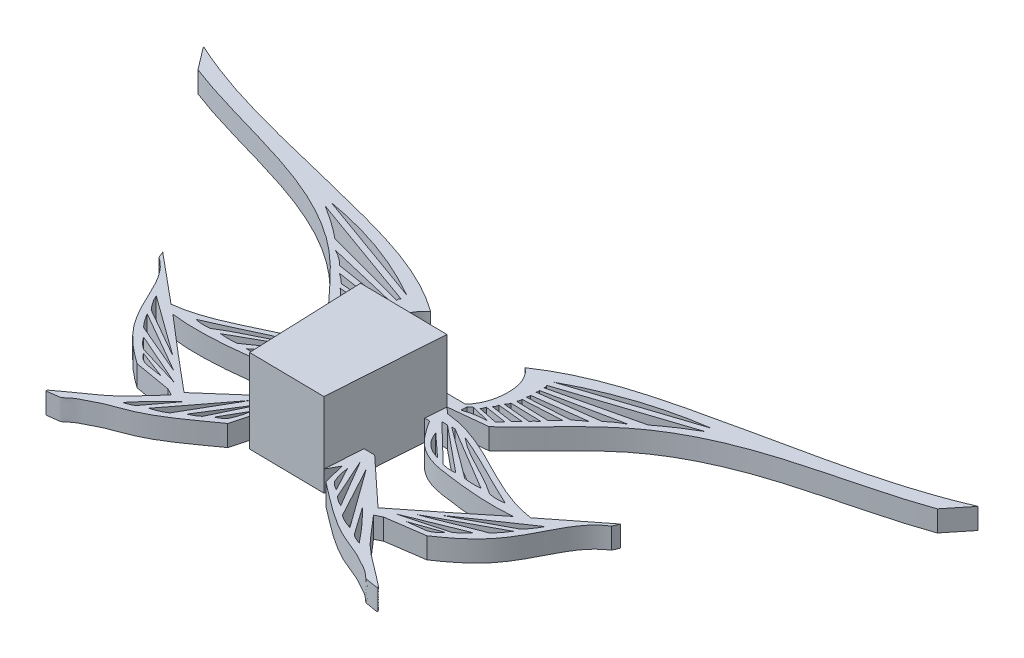
SolidWorks part; units mm, degrees
ref_plane "前视基准面" through (0, 0, 0) normal (0, 0, 1) x (1, 0, 0)
ref_plane "上视基准面" through (0, 0, 0) normal (0, 1, 0) x (1, 0, 0)
ref_plane "右视基准面" through (0, 0, 0) normal (1, 0, 0) x (0, 0, -1)
other "Configuration Table"
sketch "草图1" plane through (0, 0, 0) normal (0, 1, 0) x (1, 0, 0)
  line L0 (-16.1038, -29.8984) -> (-14.4909, -30.7553)
  line L1 (55.2168, 449.012) -> (841.2168, 449.012) construction
  line L2 (11.0888, 44.2891) -> (8.5696, -134.0017) construction
  line L3 (-35.1828, 28.1784) -> (-7.0967, 18.0952)
  line L4 (-27.2263, 21.1019) -> (-7.0967, 15.7486)
  line L6 (-21.1398, 16.1529) -> (-7.0967, 13.8965)
  line L7 (-24.774, 18.7977) -> (-7.2128, 14.6629)
  line L9 (-17.2033, 12.6101) -> (-7.0967, 11.7044)
  line L10 (-19.6184, 14.5422) -> (-7.2128, 12.6101)
  line L12 (-14.5684, 9.685) -> (-6.8789, 9.685)
  line L14 (-12.5975, 7.1733) -> (-6.0336, 7.5988)
  line L15 (-14.0695, 8.6454) -> (-6.577, 8.6454)
  line L17 (-10.5619, 5.0026) -> (-5.128, 5.6567)
  line L18 (-36.8477, -11.9893) -> (-22.4144, -22.4499)
  line L19 (-8.7638, 2.9366) -> (-4.2223, 3.7347)
  line L20 (-7.73, 2.2229) -> (-3.1356, 3.1712)
  line L21 (-16.4155, 11.532) -> (-7.0967, 10.7585)
  line L22 (-11.8701, 6.3108) -> (-5.6512, 6.7536)
  line L23 (-9.9443, 4.1171) -> (-4.6248, 4.8014)
  line L24 (-3.1356, 3.1712) -> (-2.3162, 2.539)
  line L25 (-2.3162, 2.539) -> (-2.3162, 1.0903)
  line L27 (-22.4144, -22.4499) -> (-34.4652, -15.5737)
  line L28 (-21.2778, -12.1694) -> (-5.6197, -3.4096)
  line L29 (-5.6197, -3.4096) -> (-4.7779, -3.4096)
  line L30 (-4.7779, -3.4096) -> (-17.294, -12.1857)
  line L32 (-15.0605, -12.1694) -> (-3.9079, -3.5602)
  line L33 (-3.9079, -3.5602) -> (-2.5338, -3.5602)
  line L34 (-2.5338, -3.5602) -> (-11.7753, -11.9893)
  line L35 (-9.6963, -11.3316) -> (-4.2223, -6.5835)
  line L36 (-34.191, -16.8125) -> (-19.1525, -25.4537)
  line L37 (-19.1525, -25.4537) -> (-31.8012, -20.077)
  line L38 (-29.805, -22.0591) -> (-16.8258, -27.7612)
  line L39 (-16.8258, -27.7612) -> (-27.2263, -24.6296)
  line L40 (-26.4037, -25.4537) -> (-19.6184, -28.0409)
  line L41 (-19.6184, -28.0409) -> (-23.7534, -27.401)
  line L42 (-3.9079, -22.4499) -> (-14.4158, -36.1706)
  line L43 (-16.4882, -37.1375) -> (-11.4591, -30.4187)
  line L44 (-8.6676, -32.8615) -> (-1.5765, -21.5816)
  line L45 (-4.7779, -30.2112) -> (-1.5765, -24.6296)
  line L46 (-6.3514, -31.4736) -> (-1.5765, -21.5816)
  line L47 (-10.9556, -34.6619) -> (-3.9079, -22.4499)
  line L48 (-45.0523, -2.2183) -> (-44.4505, -3.7232)
  line L49 (65.8936, -3.7859) -> (65.2495, -5.2733)
  line L50 (30.8938, -35.2532) -> (24.1939, -22.847)
  line L51 (26.3815, -31.9361) -> (21.8881, -21.9131)
  line L52 (24.8443, -30.6297) -> (21.8019, -24.9599)
  line L53 (28.6575, -33.3889) -> (21.8881, -21.9131)
  line L54 (36.3543, -37.8842) -> (31.5169, -31.026)
  line L55 (24.1939, -22.847) -> (34.31, -36.8591)
  line L56 (39.7402, -28.8797) -> (43.8916, -28.3568)
  line L57 (46.5959, -26.4851) -> (39.7402, -28.8797)
  line L58 (36.9566, -28.5211) -> (47.4415, -25.6846)
  line L59 (50.0918, -23.188) -> (36.9566, -28.5211)
  line L60 (39.3476, -26.2803) -> (52.1431, -21.2632)
  line L61 (54.6242, -18.0675) -> (39.3476, -26.2803)
  line L62 (30.2941, -11.8967) -> (24.9565, -6.9958)
  line L63 (23.3541, -3.926) -> (32.3538, -12.6128)
  line L64 (24.7277, -3.9648) -> (23.3541, -3.926)
  line L65 (35.6326, -12.8857) -> (24.7277, -3.9648)
  line L66 (25.6016, -3.8389) -> (37.8647, -12.9651)
  line L67 (26.4431, -3.8627) -> (25.6016, -3.8389)
  line L68 (41.8474, -13.0614) -> (26.4431, -3.8627)
  line L69 (42.6931, -23.3698) -> (54.9333, -16.8369)
  line L70 (23.309, 2.1769) -> (23.268, 0.7288)
  line L71 (24.1458, 2.7857) -> (23.309, 2.1769)
  line L72 (30.9785, 3.5389) -> (25.6806, 4.3732)
  line L73 (32.9655, 5.6773) -> (26.7617, 6.2956)
  line L74 (37.6567, 10.768) -> (28.3198, 10.2581)
  line L75 (28.7116, 1.708) -> (24.1458, 2.7857)
  line L76 (29.7652, 2.3922) -> (25.2481, 3.3183)
  line L77 (57.4161, -13.3212) -> (42.6931, -23.3698)
  line L78 (31.6209, 4.4066) -> (26.2077, 5.2139)
  line L79 (35.2301, 7.9488) -> (27.7406, 8.1605)
  line L80 (33.717, 6.5189) -> (27.1678, 7.1297)
  line L81 (35.7582, 8.9739) -> (28.0717, 9.1911)
  line L82 (40.9434, 13.6864) -> (28.4881, 12.1056)
  line L83 (38.4747, 11.8234) -> (28.3465, 11.2036)
  line L84 (46.2171, 17.7946) -> (28.5461, 14.1576)
  line L85 (42.5096, 15.2535) -> (28.4084, 13.3948)
  line L86 (48.7336, 20.0286) -> (28.4607, 15.2462)
  line L87 (56.8868, 26.8775) -> (28.527, 17.5919)
  line L88 (36.1745, -30.637) -> (34.538, -31.4481)
  line L89 (-1.5765, 2.8276) -> (22.5777, 2.4863)
  line L90 (-1.5765, -1.2849) -> (0, 0)
  line L91 (22.4615, -1.6245) -> (20.9219, -0.2956)
  line L92 (1.0655, -27.5848) -> (19.0775, -27.8393)
  line L93 (-1.5765, -1.2849) -> (-0.9859, -4.9581)
  line L94 (-0.9859, -4.9581) -> (21.7673, -5.2796)
  line L95 (-1.8489, -18.5408) -> (22.2462, -18.8813)
  spline S0 degree 3 poles (-0.7293, 17.4834) (-3.1453, 15.714) (-4.7785, 10.3382) (-3.3083, 4.8102) (-1.5765, 2.8276) knots 0 0 0 0 0.513587 1 1 1 1
  spline S1 degree 3 poles (-0.7293, 17.4834) (-9.9253, 24.1606) (-25.7873, 28.7225) (-53.9047, 35.5722) (-71.2957, 39.8733) (-82.7877, 45.2469) knots 0 0 0 0 0.38436 0.564437 1 1 1 1
  spline S2 degree 1 poles (-82.7877, 45.2469) (-78.5986, 39.7435) knots 0 0 1 1
  spline S3 degree 3 poles (-78.5986, 39.7435) (-66.4134, 35.0224) (-47.7039, 31.6735) (-23.6611, 18.3068) (-14.9849, 6.9582) (-9.1077, 1.2196) knots 0 0 0 0 0.482736 0.695059 1 1 1 1
  spline S4 degree 1 poles (-9.1077, 1.2196) (0, 0) knots 0 0 1 1
  spline S5 degree 3 poles (-1.5765, -1.2849) (-12.9973, -2.0584) (-21.9304, -10.6867) (-33.3037, -11.9893) knots 0 0 0 0 1 1 1 1
  spline S6 degree 1 poles (-33.3037, -11.9893) (-45.0523, -2.2183) knots 0 0 1 1
  spline S7 degree 3 poles (-44.4505, -3.7232) (-41.0317, -6.0491) (-38.1927, -12.2635) (-33.4529, -21.8525) (-28.0626, -26.2146) (-25.0609, -28.3545) knots 0 0 0 0 0.362458 0.649175 1 1 1 1
  spline S8 degree 1 poles (-25.0609, -28.3545) (-16.1038, -29.8984) knots 0 0 1 1
  spline S9 degree 3 poles (-14.4909, -30.7553) (-20.8847, -37.4993) (-18.448, -36.2364) (-31.1895, -45.0289) (-26.994, -44.4382) (-27.3576, -44.6482) (-25.2489, -42.8456) (-23.406, -42.0441) (-20.5956, -40.4291) (-12.6121, -38.0713) (-6.5286, -33.1947) (-1.8489, -29.8984) knots 0 0 0 0 0.138213 0.158314 0.168524 0.240317 0.287507 0.34345 0.409539 0.53848 1 1 1 1
  spline S10 degree 1 poles (-1.8489, -29.8984) (-0.4456, -24.7424) knots 0 0 1 1
  spline S11 degree 1 poles (-0.4456, -24.7424) (1.0655, -27.5848) knots 0 0 1 1
  spline S12 degree 3 poles (-30.9971, -13.8611) (-25.5017, -14.5037) (-17.1294, -14.0002) (-9.1527, -12.8696) (-4.2716, -9.7226) (-2.4036, -7.0417) (-0.9859, -4.9581) knots 0 0 0 0 0.52181 0.750761 0.787531 1 1 1 1
  spline S13 degree 2 poles (-30.9971, -13.8611) (-22.2983, -21.3772) (-13.459, -28.7273) knots 0 0 0 1 1 1
  spline S14 degree 1 poles (-13.459, -28.7273) (-1.8489, -18.5408) knots 0 0 1 1
  spline S15 degree 2 poles (-35.1828, 28.1784) (-20.2481, 25.6428) (-7.0967, 18.0952) knots 0 0 0 1 1 1
  spline S16 degree 2 poles (-35.1828, 26.7484) (-31.0116, 24.2005) (-27.2263, 21.1019) knots 0 0 0 1 1 1
  spline S17 degree 1 poles (-35.1828, 26.7484) (-6.9624, 16.5949) knots 0 0 1 1
  spline S18 degree 2 poles (-6.9624, 16.5949) (-7.3866, 16.2141) (-7.0967, 15.7486) knots 0 0 0 1 1 1
  spline S19 degree 2 poles (-7.2128, 14.6629) (-7.4298, 14.2488) (-7.0967, 13.8965) knots 0 0 0 1 1 1
  spline S20 degree 2 poles (-7.2128, 12.6101) (-7.3464, 12.1186) (-7.0967, 11.7044) knots 0 0 0 1 1 1
  spline S21 degree 2 poles (-7.0967, 10.7585) (-7.2103, 10.1725) (-6.8789, 9.685) knots 0 0 0 1 1 1
  spline S22 degree 2 poles (-6.577, 8.6454) (-6.5886, 7.9876) (-6.0336, 7.5988) knots 0 0 0 1 1 1
  spline S23 degree 2 poles (-5.6512, 6.7536) (-5.724, 6.0801) (-5.128, 5.6567) knots 0 0 0 1 1 1
  spline S24 degree 3 poles (-27.2263, -12.1694) (-20.9503, -9.5199) (-14.926, -6.273) (-8.5381, -3.8842) knots 0 0 0 0 1 1 1 1
  spline S25 degree 3 poles (-8.5381, -3.8842) (-13.1033, -7.473) (-18.7599, -9.1308) (-23.5809, -12.2986) knots 0 0 0 0 1 1 1 1
  spline S26 degree 2 poles (-15.0605, -12.1694) (-13.3879, -12.4146) (-11.7753, -11.9893) knots 0 0 0 1 1 1
  spline S27 degree 2 poles (-21.2778, -12.1694) (-19.2849, -12.4221) (-17.294, -12.1857) knots 0 0 0 1 1 1
  spline S28 degree 2 poles (-27.2263, -12.1694) (-25.4052, -12.5568) (-23.5809, -12.2986) knots 0 0 0 1 1 1
  spline S29 degree 2 poles (-4.2223, -6.5835) (-5.6759, -10.4126) (-9.6963, -11.3316) knots 0 0 0 1 1 1
  spline S30 degree 2 poles (-24.774, 18.7977) (-22.7376, 17.7531) (-21.1398, 16.1529) knots 0 0 0 1 1 1
  spline S31 degree 2 poles (-19.6184, 14.5422) (-18.3287, 13.6785) (-17.2033, 12.6101) knots 0 0 0 1 1 1
  spline S32 degree 2 poles (-16.4155, 11.532) (-15.3902, 10.7078) (-14.5684, 9.685) knots 0 0 0 1 1 1
  spline S33 degree 2 poles (-14.0695, 8.6454) (-13.2207, 8.0185) (-12.5975, 7.1733) knots 0 0 0 1 1 1
  spline S34 degree 2 poles (-11.8701, 6.3108) (-11.1648, 5.7068) (-10.5619, 5.0026) knots 0 0 0 1 1 1
  spline S35 degree 2 poles (-9.9443, 4.1171) (-9.3284, 3.5521) (-8.7638, 2.9366) knots 0 0 0 1 1 1
  spline S36 degree 2 poles (-7.73, 2.2229) (-4.9085, 2.1238) (-2.3162, 1.0903) knots 0 0 0 1 1 1
  spline S37 degree 2 poles (-36.8477, -11.9893) (-35.9291, -13.9781) (-34.4652, -15.5737) knots 0 0 0 1 1 1
  spline S38 degree 2 poles (-34.191, -16.8125) (-33.1483, -18.558) (-31.8012, -20.077) knots 0 0 0 1 1 1
  spline S39 degree 2 poles (-29.805, -22.0591) (-28.7536, -23.5703) (-27.2263, -24.6296) knots 0 0 0 1 1 1
  spline S40 degree 2 poles (-26.4037, -25.4537) (-25.455, -26.96) (-23.7534, -27.401) knots 0 0 0 1 1 1
  spline S41 degree 2 poles (-14.4158, -36.1706) (-12.5462, -35.7028) (-10.9556, -34.6619) knots 0 0 0 1 1 1
  spline S42 degree 2 poles (-8.6676, -32.8615) (-7.3979, -32.3437) (-6.3514, -31.4736) knots 0 0 0 1 1 1
  spline S43 degree 2 poles (-4.7779, -30.2112) (-3.5827, -29.7227) (-2.7802, -28.7273) knots 0 0 0 1 1 1
  spline S44 degree 2 poles (-11.4591, -30.4187) (-15.3686, -34.0532) (-18.795, -38.1409) knots 0 0 0 1 1 1
  spline S45 degree 2 poles (-18.795, -38.1409) (-17.5646, -37.8119) (-16.4882, -37.1375) knots 0 0 0 1 1 1
  spline S46 degree 2 poles (-1.5765, -24.6296) (-1.8193, -26.8002) (-2.7802, -28.7273) knots 0 0 0 1 1 1
  spline S47 degree 2 poles (21.8019, -24.9599) (21.9833, -27.1365) (22.8893, -29.09) knots 0 0 0 1 1 1
  spline S48 degree 2 poles (38.6318, -38.9523) (37.4111, -38.5887) (36.3543, -37.8842) knots 0 0 0 1 1 1
  spline S49 degree 2 poles (31.5169, -31.026) (35.3222, -34.7695) (38.6318, -38.9523) knots 0 0 0 1 1 1
  spline S50 degree 2 poles (24.8443, -30.6297) (23.6634, -30.1076) (22.8893, -29.09) knots 0 0 0 1 1 1
  spline S51 degree 2 poles (28.6575, -33.3889) (27.403, -32.8355) (26.3815, -31.9361) knots 0 0 0 1 1 1
  spline S52 degree 2 poles (34.31, -36.8591) (32.4544, -36.3387) (30.8938, -35.2532) knots 0 0 0 1 1 1
  spline S53 degree 2 poles (46.5959, -26.4851) (45.605, -27.9641) (43.8916, -28.3568) knots 0 0 0 1 1 1
  spline S54 degree 2 poles (50.0918, -23.188) (48.998, -24.6689) (47.4415, -25.6846) knots 0 0 0 1 1 1
  spline S55 degree 2 poles (54.6242, -18.0675) (53.5327, -19.7828) (52.1431, -21.2632) knots 0 0 0 1 1 1
  spline S56 degree 2 poles (57.4161, -13.3212) (56.4417, -15.2833) (54.9333, -16.8369) knots 0 0 0 1 1 1
  spline S57 degree 2 poles (28.7116, 1.708) (25.8885, 1.6886) (23.268, 0.7288) knots 0 0 0 1 1 1
  spline S58 degree 2 poles (30.9785, 3.5389) (30.3469, 2.9915) (29.7652, 2.3922) knots 0 0 0 1 1 1
  spline S59 degree 2 poles (32.9655, 5.6773) (32.2435, 5.0935) (31.6209, 4.4066) knots 0 0 0 1 1 1
  spline S60 degree 2 poles (35.2301, 7.9488) (34.3639, 7.3462) (33.717, 6.5189) knots 0 0 0 1 1 1
  spline S61 degree 2 poles (37.6567, 10.768) (36.6085, 9.9731) (35.7582, 8.9739) knots 0 0 0 1 1 1
  spline S62 degree 2 poles (40.9434, 13.6864) (39.6298, 12.8595) (38.4747, 11.8234) knots 0 0 0 1 1 1
  spline S63 degree 2 poles (46.2171, 17.7946) (44.152, 16.808) (42.5096, 15.2535) knots 0 0 0 1 1 1
  spline S64 degree 2 poles (24.9565, -6.9958) (26.3014, -10.8644) (30.2941, -11.8967) knots 0 0 0 1 1 1
  spline S65 degree 2 poles (47.7935, -13.2294) (45.9621, -13.5652) (44.1459, -13.2556) knots 0 0 0 1 1 1
  spline S66 degree 2 poles (41.8474, -13.0614) (39.8481, -13.2577) (37.8647, -12.9651) knots 0 0 0 1 1 1
  spline S67 degree 2 poles (35.6326, -12.8857) (33.9537, -13.0835) (32.3538, -12.6128) knots 0 0 0 1 1 1
  spline S68 degree 3 poles (29.3469, -4.4195) (33.8089, -8.1358) (39.4163, -9.9528) (44.1459, -13.2556) knots 0 0 0 0 1 1 1 1
  spline S69 degree 3 poles (47.7935, -13.2294) (41.5949, -10.4036) (35.6648, -6.9878) (29.3469, -4.4195) knots 0 0 0 0 1 1 1 1
  spline S70 degree 2 poles (26.7617, 6.2956) (26.8154, 5.6203) (26.2077, 5.2139) knots 0 0 0 1 1 1
  spline S71 degree 2 poles (27.7406, 8.1605) (27.7335, 7.5027) (27.1678, 7.1297) knots 0 0 0 1 1 1
  spline S72 degree 2 poles (28.3198, 10.2581) (28.4167, 9.6691) (28.0717, 9.1911) knots 0 0 0 1 1 1
  spline S73 degree 2 poles (28.4881, 12.1056) (28.6078, 11.6106) (28.3465, 11.2036) knots 0 0 0 1 1 1
  spline S74 degree 2 poles (28.5461, 14.1576) (28.7513, 13.7375) (28.4084, 13.3948) knots 0 0 0 1 1 1
  spline S75 degree 2 poles (28.3504, 16.0959) (28.7636, 15.7033) (28.4607, 15.2462) knots 0 0 0 1 1 1
  spline S76 degree 1 poles (56.8464, 25.4481) (28.3504, 16.0959) knots 0 0 1 1
  spline S77 degree 2 poles (56.8464, 25.4481) (52.6049, 23.019) (48.7336, 20.0286) knots 0 0 0 1 1 1
  spline S78 degree 2 poles (56.8868, 26.8775) (41.8864, 24.7649) (28.527, 17.5919) knots 0 0 0 1 1 1
  spline S79 degree 1 poles (33.5639, -29.3917) (22.2462, -18.8813) knots 0 0 1 1
  spline S80 degree 2 poles (51.515, -15.027) (42.6074, -22.2943) (33.5639, -29.3917) knots 0 0 0 1 1 1
  spline S81 degree 3 poles (51.515, -15.027) (46.0037, -15.5141) (37.6489, -14.7742) (29.7073, -13.4187) (24.9171, -10.1351) (23.1256, -7.4024) (21.7673, -5.2796) knots 0 0 0 0 0.52181 0.750761 0.787531 1 1 1 1
  spline S82 degree 1 poles (20.6683, -25.0407) (19.0775, -27.8393) knots 0 0 1 1
  spline S83 degree 1 poles (21.9253, -30.2343) (20.6683, -25.0407) knots 0 0 1 1
  spline S84 degree 3 poles (34.538, -31.4481) (40.7387, -38.37) (38.3387, -37.0388) (50.8267, -46.1878) (46.6495, -45.4788) (47.0071, -45.6989) (44.9501, -43.8375) (43.1306, -42.9842) (40.367, -41.2905) (32.4533, -38.7081) (26.51, -33.6615) (21.9253, -30.2343) knots 0 0 0 0 0.138213 0.158314 0.168524 0.240317 0.287507 0.34345 0.409539 0.53848 1 1 1 1
  spline S85 degree 1 poles (45.1717, -29.3469) (36.1745, -30.637) knots 0 0 1 1
  spline S86 degree 3 poles (65.2495, -5.2733) (61.7663, -7.5016) (58.7529, -13.6333) (53.744, -23.0846) (48.2326, -27.2926) (45.1717, -29.3469) knots 0 0 0 0 0.362458 0.649175 1 1 1 1
  spline S87 degree 1 poles (53.8736, -13.2211) (65.8936, -3.7859) knots 0 0 1 1
  spline S88 degree 3 poles (22.4615, -1.6245) (33.8558, -2.7204) (42.5416, -11.5977) (53.8736, -13.2211) knots 0 0 0 0 1 1 1 1
  spline S89 degree 1 poles (30.0604, 0.6662) (20.9219, -0.2956) knots 0 0 1 1
  spline S90 degree 3 poles (100.612, 37.2113) (88.2983, 32.8364) (69.5017, 30.0175) (45.0908, 17.3354) (36.0974, 6.2364) (30.0604, 0.6662) knots 0 0 0 0 0.482736 0.695059 1 1 1 1
  spline S91 degree 1 poles (104.955, 42.5942) (100.612, 37.2113) knots 0 0 1 1
  spline S92 degree 3 poles (22.1449, 17.1602) (31.5259, 23.5749) (47.5104, 27.6868) (75.8101, 33.7394) (93.3157, 37.5474) (104.955, 42.5942) knots 0 0 0 0 0.38436 0.564437 1 1 1 1
  spline S93 degree 3 poles (22.1449, 17.1602) (24.5099, 15.3232) (25.9906, 9.9034) (24.3648, 4.4192) (22.5777, 2.4863) knots 0 0 0 0 0.513587 1 1 1 1
  spline S94 degree 2 poles (-4.6248, 4.8014) (-4.4766, 4.2472) (-4.2223, 3.7347) knots 0 0 0 1 1 1
  spline S95 degree 2 poles (25.6806, 4.3732) (25.5562, 3.8046) (25.2481, 3.3183) knots 0 0 0 1 1 1
  point P159 (0, 0)
extrude "凸台-拉伸2" add sketch "草图1" along normal blind 5
sketch "草图15" plane through (0, 0, 0) normal (0, 1, 0) x (1, 0, 0)
  line L0 (11.0093, 39.519) -> (9.6389, -57.4713) construction
  line L1 (-1.5765, 2.8276) -> (22.5777, 2.4863) construction
  line L2 (0, 0) -> (1.0655, -27.5848)
  line L3 (1.0655, -27.5848) -> (19.0775, -27.8393)
  line L4 (19.0775, -27.8393) -> (20.9219, -0.2956)
  line L5 (20.9219, -0.2956) -> (0, 0)
extrude "凸台-拉伸4" add sketch "草图15" along normal blind 20
